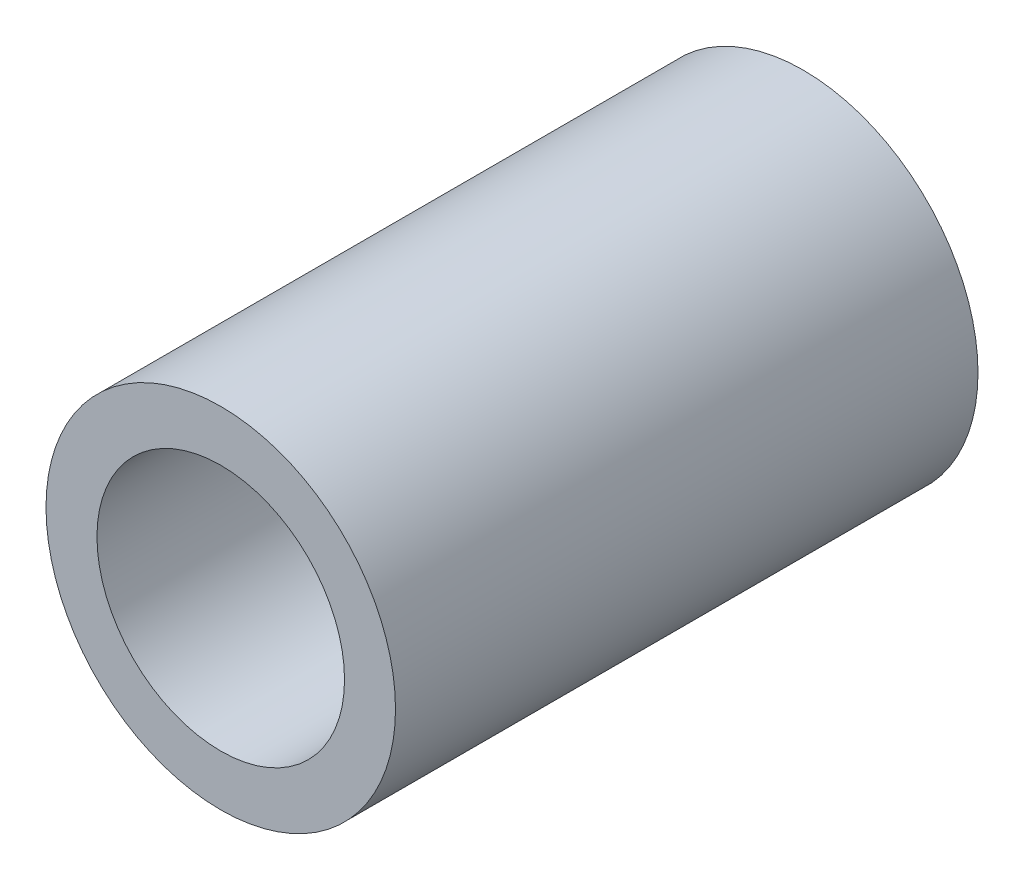
SolidWorks part; units mm, degrees
ref_plane "Front Plane" through (0, 0, 0) normal (0, 0, 1) x (1, 0, 0)
ref_plane "Top Plane" through (0, 0, 0) normal (0, 1, 0) x (1, 0, 0)
ref_plane "Right Plane" through (0, 0, 0) normal (1, 0, 0) x (0, 0, -1)
sketch "Sketch1" plane through (0, 0, 0) normal (0, 0, 1) x (1, 0, 0)
  circle A1 centre (33, 0) radius 4.25
  circle A2 centre (33, 0) radius 6
  dimension "D2" = 8.5
  dimension "D1" = 12
extrude "Boss-Extrude1" add sketch "Sketch1" along normal blind 20
